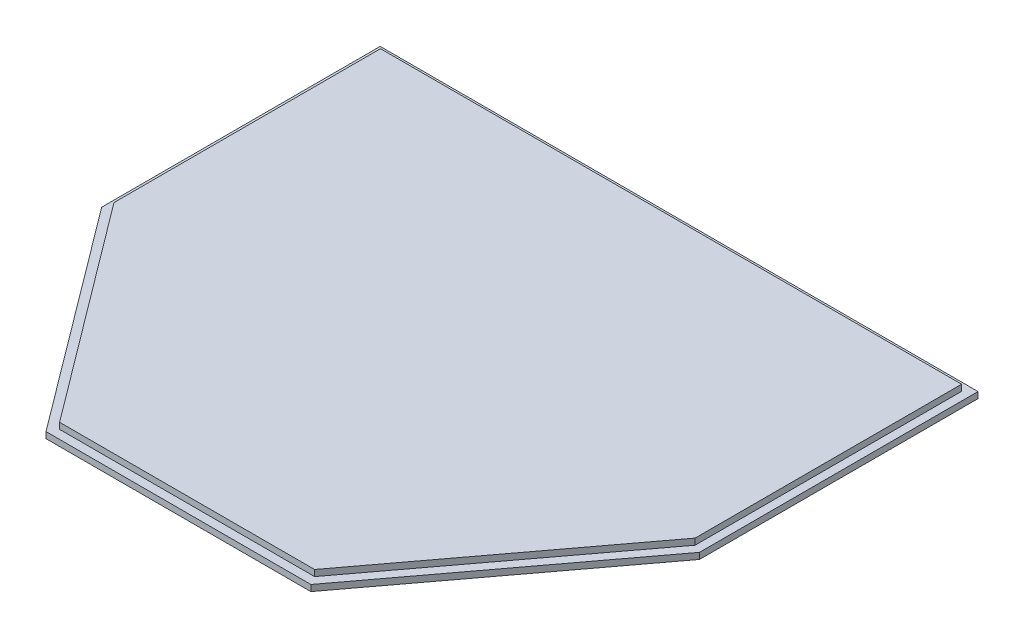
SolidWorks part; units mm, degrees
ref_plane "前视基准面" through (0, 0, 0) normal (0, 0, 1) x (1, 0, 0)
ref_plane "上视基准面" through (0, 0, 0) normal (0, 1, 0) x (1, 0, 0)
ref_plane "右视基准面" through (0, 0, 0) normal (1, 0, 0) x (0, 0, -1)
sketch "草图1" plane through (0, 0, 0) normal (0, 1, 0) x (1, 0, 0)
  line L0 (0, 0) -> (0, -404.5) construction
  line L1 (-241.5, 0) -> (241.5, 0)
  line L2 (241.5, 0) -> (241.5, -225)
  line L3 (241.5, -225) -> (107, -404.5)
  line L4 (107, -404.5) -> (-107, -404.5)
  line L5 (-241.5, -225) -> (-107, -404.5)
  line L6 (-241.5, 0) -> (-241.5, -225)
  dimension "D1" = 404.5
  dimension "D2" = 483
  dimension "D3" = 225
  dimension "D4" = 214
extrude "凸台-拉伸1" add sketch "草图1" along normal blind 5
sketch "草图2" plane through (0, 5, 0) normal (0, 1, 0) x (1, 0, 0)
  line L0 (-234.75, -6.5) -> (234.75, -6.5)
  line L1 (234.75, -6.5) -> (234.75, -221.8333)
  line L2 (234.75, -221.8333) -> (103, -397.5)
  line L3 (103, -397.5) -> (-103, -397.5)
  line L4 (-103, -397.5) -> (-234.75, -221.8333)
  line L5 (-234.75, -221.8333) -> (-234.75, -6.5)
  line L7 (0, -397.5) -> (0, 0) construction
  line L8 (241.5, 0) -> (-241.5, 0) construction
  point P9 (0, -6.5)
  point P12 (0, 0)
  dimension "D1" = 469.5
  dimension "D2" = 391
  dimension "D3" = 6.5
  dimension "D4" = 206
  dimension "D5" = 53.13
  dimension "D6" = 53.13
  dimension "D7" = 131.75
  dimension "D8" = 175.6667
extrude "凸台-拉伸2" add sketch "草图2" along normal blind 5
equation "\"D5@草图2\"=arcsin( 0.8)"
equation "\"D6@草图2\"=arcsin( 0.8)"
